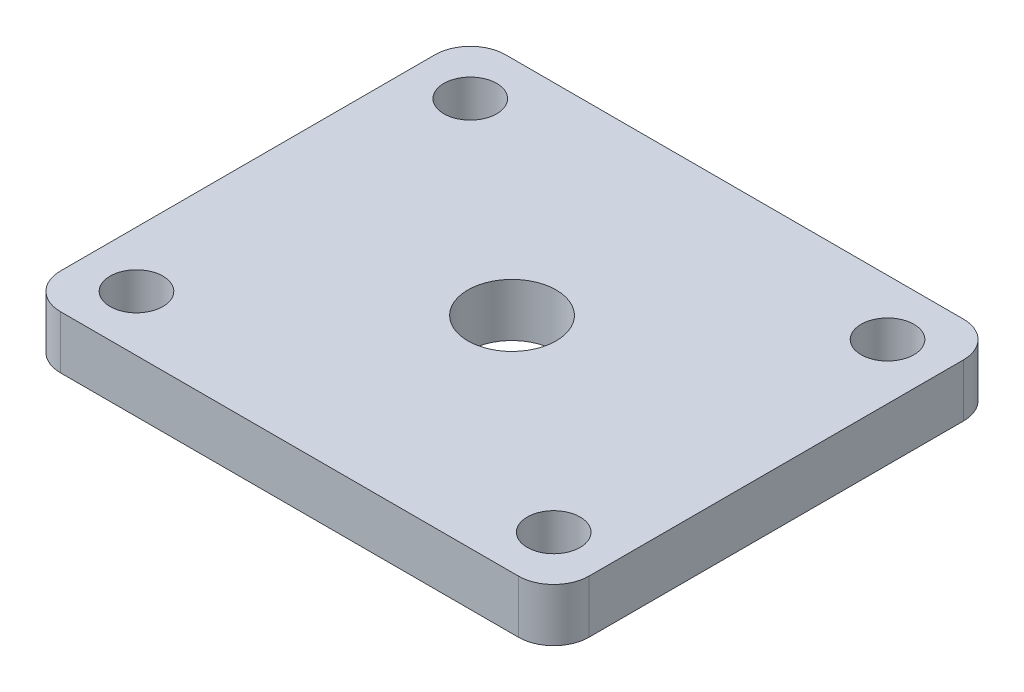
SolidWorks part; units mm, degrees
ref_plane "Front Plane" through (0, 0, 0) normal (0, 0, 1) x (1, 0, 0)
ref_plane "Top Plane" through (0, 0, 0) normal (0, 1, 0) x (1, 0, 0)
ref_plane "Right Plane" through (0, 0, 0) normal (1, 0, 0) x (0, 0, -1)
sketch "Sketch2" plane through (0, 0, 0) normal (0, 1, 0) x (1, 0, 0)
  line L0 (19, 32) -> (19, 0) construction
  line L1 (0, 0) -> (38, 0)
  line L2 (0, 0) -> (0, 32)
  line L3 (0, 32) -> (38, 32)
  line L4 (38, 0) -> (38, 32)
  line L5 (0, 16) -> (38, 16) construction
  line L6 (4, 4) -> (34, 4) construction
  line L7 (34, 4) -> (34, 28) construction
  line L8 (34, 28) -> (4, 28) construction
  line L9 (4, 28) -> (4, 4) construction
  circle A0 centre (19, 16) radius 3.175
  circle A1 centre (4, 4) radius 1.8987
  circle A2 centre (4, 28) radius 1.8987
  circle A3 centre (34, 28) radius 1.8986
  circle A4 centre (34, 4) radius 1.8986
  point P19 (19, 4)
  point P20 (34, 16)
  dimension "D3" = 6.35
  dimension "D4" = 3.7973
  dimension "D1" = 38
  dimension "D2" = 32
  dimension "D5" = 24
  dimension "D6" = 30
extrude "Boss-Extrude1" add sketch "Sketch2" along normal blind 3.81
fillet "Fillet1" radius 2.54 4 edges at (0, 1.905, -32) (38, 1.905, -32) (38, 1.905, 0) (0, 1.905, 0)
